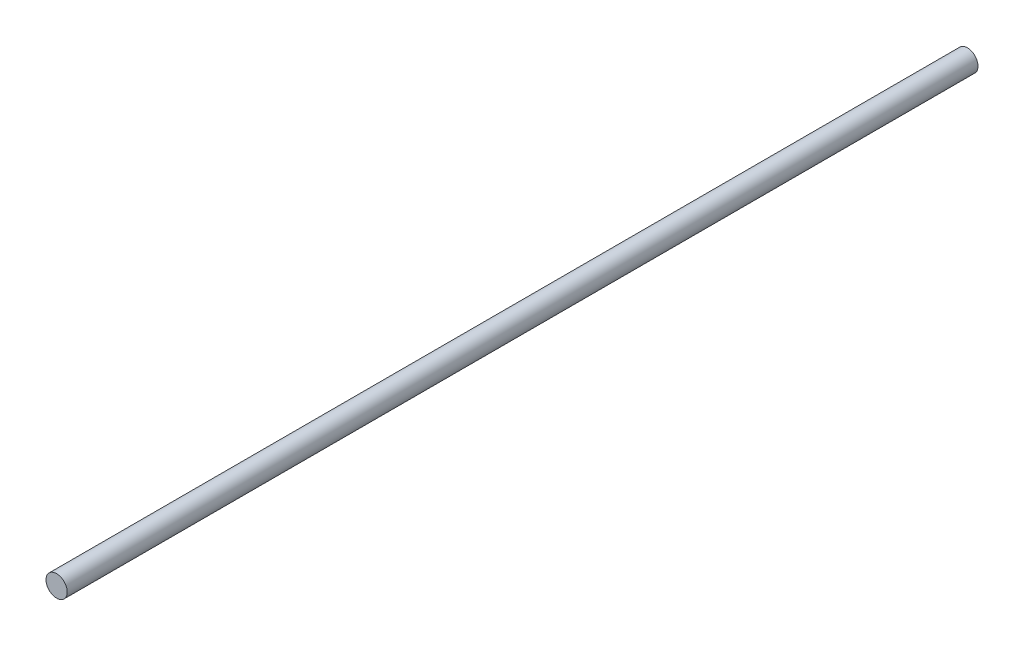
SolidWorks part; units mm, degrees
ref_plane "Front Plane" through (0, 0, 0) normal (0, 0, 1) x (1, 0, 0)
ref_plane "Top Plane" through (0, 0, 0) normal (0, 1, 0) x (1, 0, 0)
ref_plane "Right Plane" through (0, 0, 0) normal (1, 0, 0) x (0, 0, -1)
sketch "Sketch2" plane through (0, 0, 0) normal (0, 0, 1) x (1, 0, 0)
  circle A0 centre (0, 0) radius 17.5
  dimension "D1" = 35
extrude "Boss-Extrude1" add sketch "Sketch2" against normal blind 1500
